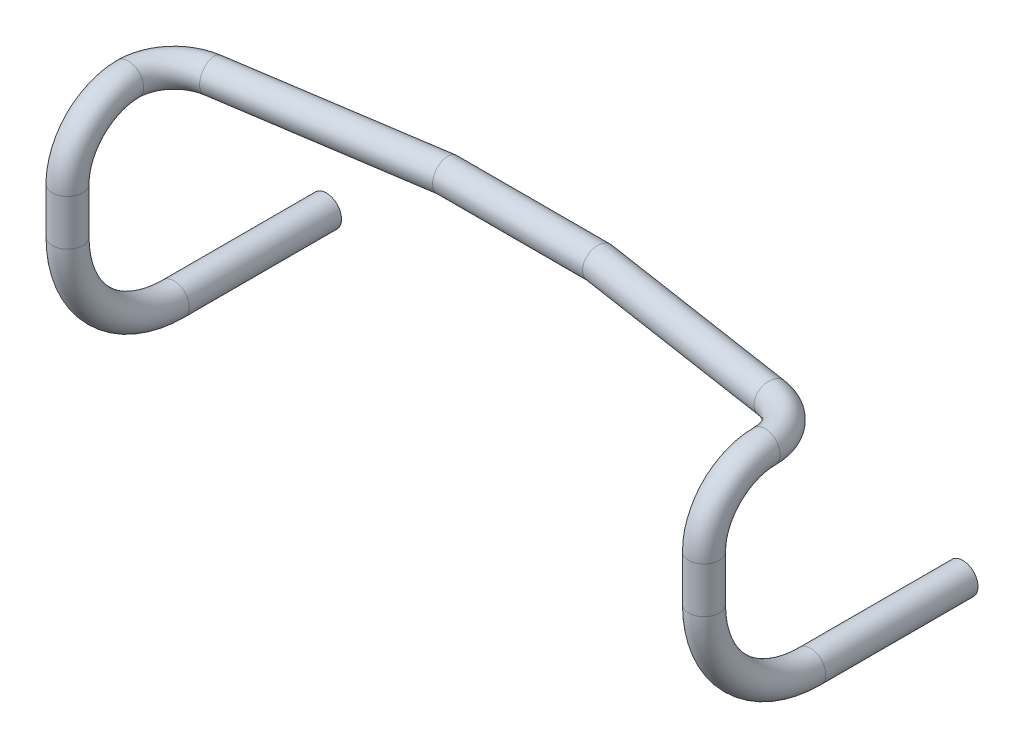
SolidWorks part; units mm, degrees
material "Aluminum Bronze"
ref_plane "Front Plane" through (0, 0, 0) normal (0, 0, 1) x (1, 0, 0)
ref_plane "Top Plane" through (0, 0, 0) normal (0, 1, 0) x (1, 0, 0)
ref_plane "Right Plane" through (0, 0, 0) normal (1, 0, 0) x (0, 0, -1)
sketch3d "3DSketch1"
  line L0 (-50, 0, 0) -> (50, 0, 0)
  line L1 (50, 0, 0) -> (183.5625, 0, 20.342)
  line L2 (209.0454, -40, 90) -> (209.0454, -70, 90)
  line L3 (209.0454, -140, 20) -> (209.0454, -140, -80)
  line L4 (-44.6229, 0, 20) -> (44.6229, 0, 20) construction
  line L5 (-209.0454, -140, 20) -> (-209.0454, -140, -80)
  line L6 (-209.0454, -40, 90) -> (-209.0454, -70, 90)
  line L7 (-50, 0, 0) -> (-183.5625, 0, 20.342)
  arc A0 (183.5625, 0, 20.342) -> (209.0454, 0, 50) centre (179.0454, 0, 50) ccw
  arc A1 (209.0454, 0, 50) -> (209.0454, -40, 90) centre (209.0454, -40, 50) ccw
  arc A2 (209.0454, -70, 90) -> (209.0454, -140, 20) centre (209.0454, -70, 20) ccw
  arc A3 (-209.0454, -140, 20) -> (-209.0454, -70, 90) centre (-209.0454, -70, 20) cw
  arc A4 (-209.0454, -40, 90) -> (-209.0454, 0, 50) centre (-209.0454, -40, 50) cw
  arc A5 (-209.0454, 0, 50) -> (-183.5625, 0, 20.342) centre (-179.0454, 0, 50) cw
  point P0 (-209.0454, 0, 20)
  point P5 (179.0454, -30, 50)
  point P8 (249.0454, -40, 50)
  point P12 (279.0454, -70, 20)
  point P15 (209.0454, 0, 90)
  point P16 (209.0454, -140, 90)
  point P17 (209.0454, 0, 20)
  point P21 (0, 0, 20)
  point P24 (-279.0454, -70, 20)
  point P28 (-249.0454, -40, 50)
  point P31 (-179.0454, -30, 50)
  point P34 (0, 0, 0)
  point P35 (-209.0454, -140, 90)
  point P36 (-209.0454, 0, 90)
  dimension "D1" = 30
  dimension "D2" = 70
  dimension "D5" = 40
  dimension "D3" = 170
  dimension "D4" = 140
  dimension "D6" = 210
  dimension "D7" = 20
  dimension "D8" = 50
ref_plane "Plane1" through (0, 0, -80) normal (0, 0, 1) x (1, 0, 0)
sketch "Sketch1" plane through (0, 0, -80) normal (0, 0, 1) x (1, 0, 0)
  circle A0 centre (-209.0454, -140) radius 10
  dimension "D1" = 20
sweep "Sweep1" add profiles "Sketch1" path "3DSketch1"
